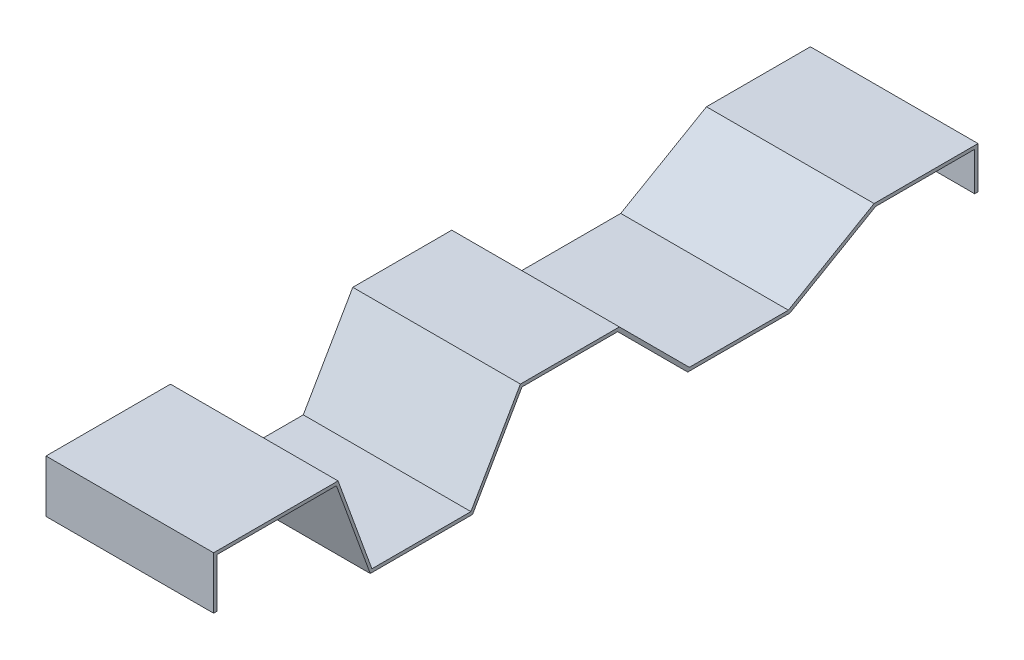
SolidWorks part; units mm, degrees
ref_plane "Front Plane" through (0, 0, 0) normal (0, 0, 1) x (1, 0, 0)
ref_plane "Top Plane" through (0, 0, 0) normal (0, 1, 0) x (1, 0, 0)
ref_plane "Right Plane" through (0, 0, 0) normal (1, 0, 0) x (0, 0, -1)
sketch "Sketch1" plane through (0, 0, 0) normal (1, 0, 0) x (0, 0, -1)
  line L0 (410.976, -727.738) -> (410.976, -702.338)
  line L1 (410.976, -702.338) -> (347.984, -702.338)
  line L2 (347.984, -702.338) -> (296.0225, -732.338)
  line L3 (296.0225, -732.338) -> (236.0225, -732.338)
  line L4 (236.0225, -732.338) -> (193.596, -689.9116)
  line L5 (193.596, -689.9116) -> (133.596, -689.9116)
  line L6 (133.596, -689.9116) -> (103.596, -741.8731)
  line L7 (103.596, -741.8731) -> (43.596, -741.8731)
  line L8 (43.596, -741.8731) -> (23.0748, -685.4916)
  line L9 (23.0748, -685.4916) -> (-52.3632, -685.4916)
  line L10 (-52.3632, -685.4916) -> (-52.3632, -717.2416)
  line L11 (410.976, -727.738) -> (408.976, -727.738)
  line L12 (408.976, -727.738) -> (408.976, -704.338)
  line L13 (408.976, -704.338) -> (348.976, -704.338)
  line L14 (348.976, -704.338) -> (297.0145, -734.338)
  line L15 (297.0145, -734.338) -> (235.0145, -734.338)
  line L16 (235.0145, -734.338) -> (192.588, -691.9116)
  line L17 (192.588, -691.9116) -> (134.588, -691.9116)
  line L18 (134.588, -691.9116) -> (104.588, -743.8731)
  line L19 (104.588, -743.8731) -> (42.588, -743.8731)
  line L20 (42.588, -743.8731) -> (22.0668, -687.4916)
  line L21 (22.0668, -687.4916) -> (-50.3632, -687.4916)
  line L22 (-50.3632, -687.4916) -> (-50.3632, -717.2416)
  line L23 (-50.3632, -717.2416) -> (-52.3632, -717.2416)
  dimension "D1" = 62.992
  dimension "D2" = 60
  dimension "D3" = 60
  dimension "D4" = 60
  dimension "D5" = 60
  dimension "D6" = 120
  dimension "D7" = 60
  dimension "D8" = 150
  dimension "D9" = 135
  dimension "D10" = 60
  dimension "D11" = 25.4
  dimension "D12" = 110
  dimension "D13" = 60
  dimension "D14" = 75.438
  dimension "D15" = 31.75
  dimension "D16" = 2
  dimension "D17" = 2
  dimension "D18" = 2
  dimension "D19" = 150
  dimension "D20" = 135
  dimension "D21" = 120
  dimension "D22" = 110
  dimension "D23" = 2
  dimension "D24" = 60
  dimension "D25" = 2
  dimension "D26" = 62
  dimension "D27" = 58
  dimension "D28" = 60
  dimension "D29" = 2
  dimension "D30" = 62
extrude "Boss-Extrude1" add sketch "Sketch1" along normal blind 101.6
